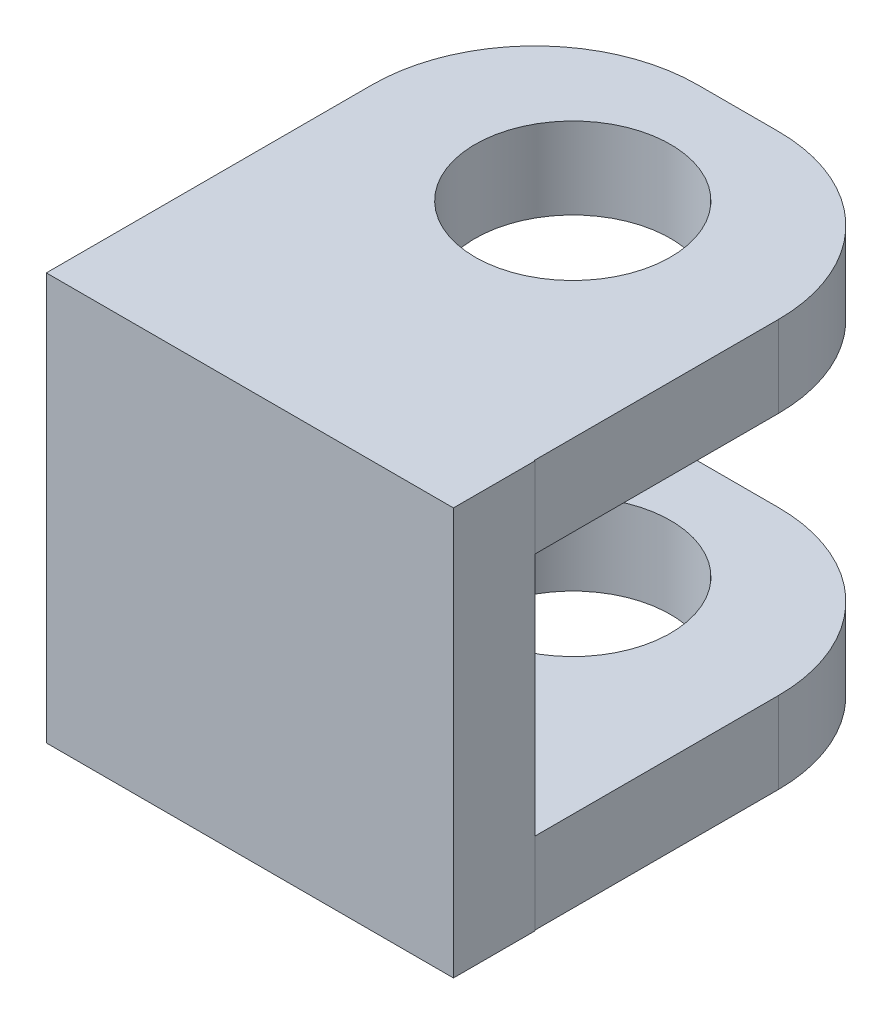
SolidWorks part; units mm, degrees
ref_plane "Front Plane" through (0, 0, 0) normal (0, 0, 1) x (1, 0, 0)
ref_plane "Top Plane" through (0, 0, 0) normal (0, 1, 0) x (1, 0, 0)
ref_plane "Right Plane" through (0, 0, 0) normal (1, 0, 0) x (0, 0, -1)
sketch "Sketch1" plane through (0, 0, 0) normal (0, 0, 1) x (1, 0, 0)
  line L1 (0, 0) -> (50, 0)
  line L2 (0, 0) -> (0, 50)
  line L3 (0, 50) -> (50, 50)
  line L4 (50, 0) -> (50, 50)
  dimension "D1" = 50
  dimension "D2" = 50
extrude "Boss-Extrude1" add sketch "Sketch1" along normal blind 10
sketch "Sketch2" plane through (0, 0, 0) normal (0, 1, 0) x (1, 0, 0)
  line L1 (0, 0) -> (49.911, 0)
  line L2 (0, 0) -> (0, 30)
  line L3 (20, 50) -> (29.911, 50)
  line L4 (49.911, 0) -> (49.911, 30)
  arc A0 (29.911, 50) -> (49.911, 30) centre (29.911, 30) cw
  arc A1 (20, 50) -> (0, 30) centre (20, 30) ccw
  point P7 (49.911, 50)
  dimension "D2" = 20
  dimension "D1" = 50
extrude "Boss-Extrude2" add sketch "Sketch2" along normal blind 10
sketch "Sketch3" plane through (0, 50, 0) normal (0, 1, 0) x (1, 0, 0)
  line L0 (49.911, 0) -> (49.911, 30) construction
  line L1 (0, 0) -> (49.911, 0)
  line L2 (0, 0) -> (0, 30)
  line L3 (20, 50) -> (29.911, 50)
  line L4 (49.911, 0) -> (49.911, 30)
  arc A0 (49.911, 30) -> (29.911, 50) centre (29.911, 30) ccw
  arc A1 (20, 50) -> (0, 30) centre (20, 30) ccw
  point P9 (49.911, 50)
  point P12 (0, 50)
  dimension "D2" = 20
  dimension "D1" = 50
extrude "Boss-Extrude3" add sketch "Sketch3" against normal blind 10
sketch "Sketch4" plane through (0, 50, 0) normal (0, 1, 0) x (1, 0, 0)
  circle A1 centre (24.659, 30) radius 12
  point P0 (0, 0)
extrude "Cut-Extrude2" cut sketch "Sketch4" against normal blind 120
